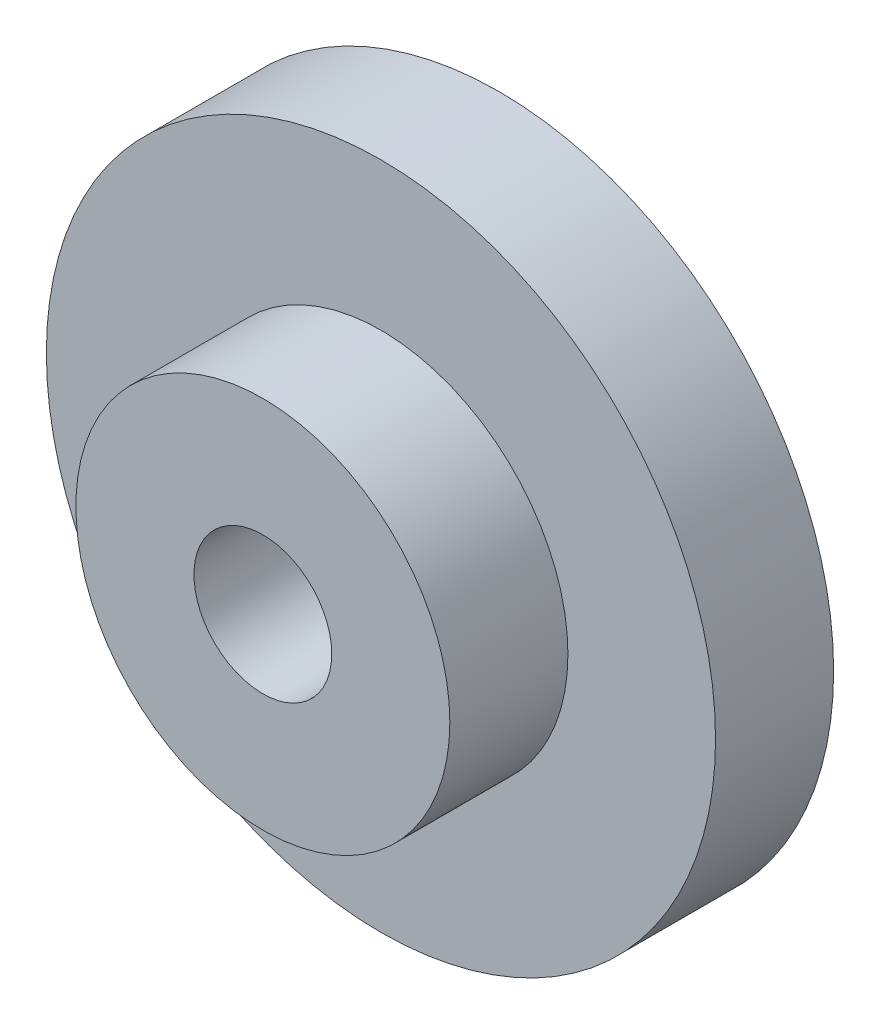
SolidWorks part; units mm, degrees
ref_plane "Front Plane" through (0, 0, 0) normal (0, 0, 1) x (1, 0, 0)
ref_plane "Top Plane" through (0, 0, 0) normal (0, 1, 0) x (1, 0, 0)
ref_plane "Right Plane" through (0, 0, 0) normal (1, 0, 0) x (0, 0, -1)
sketch "Sketch1" plane through (0, 0, 0) normal (1, 0, 0) x (0, 0, -1)
  line L0 (-3.3548, 0) -> (2.6452, 0)
  line L1 (2.6452, 0) -> (2.6452, 6.75)
  line L2 (2.6452, 6.75) -> (-0.3548, 6.75)
  line L3 (-0.3548, 6.75) -> (-0.3548, 3)
  line L4 (-0.3548, 3) -> (-3.3548, 3)
  line L5 (-3.3548, 3) -> (-3.3548, 0)
  line L6 (-3.3548, -1.75) -> (2.6452, -1.75) construction
  dimension "D1" = 3
  dimension "D2" = 1.75
  dimension "D3" = 4.75
  dimension "D4" = 3.75
revolve "Revolve1" add sketch "Sketch1" angle 360 about L6
